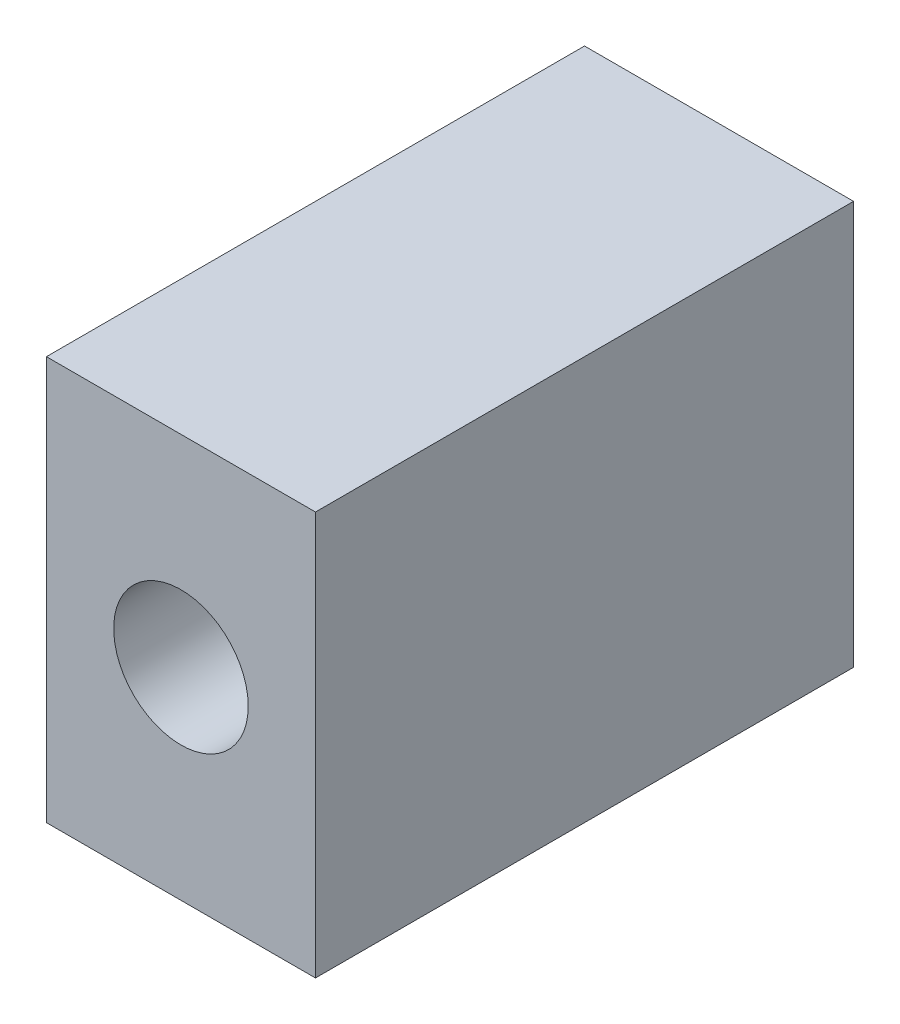
SolidWorks part; units mm, degrees
ref_plane "Front Plane" through (0, 0, 0) normal (0, 0, 1) x (1, 0, 0)
ref_plane "Top Plane" through (0, 0, 0) normal (0, 1, 0) x (1, 0, 0)
ref_plane "Right Plane" through (0, 0, 0) normal (1, 0, 0) x (0, 0, -1)
ref_plane "plane:base-xy" through (0, 0, 0) normal (0, 0, 1) x (1, 0, 0)
sketch "sketch:base-profile" plane through (0, 0, 0) normal (0, 0, 1) x (1, 0, 0)
  line L0 (0, 0) -> (20, 0)
  line L1 (20, 0) -> (20, 30)
  line L2 (20, 30) -> (0, 30)
  line L3 (0, 30) -> (0, 0)
extrude "feature:base" add sketch "sketch:base-profile" along normal blind 40 separate body
ref_plane "plane:top-xy" through (0, 0, 40) normal (0, 0, 1) x (1, 0, 0)
sketch "sketch:hole-profile" plane through (0, 0, 40) normal (0, 0, 1) x (1, 0, 0)
  circle A0 centre (10, 15) radius 5
extrude "feature:through-hole" cut sketch "sketch:hole-profile" against normal through all
